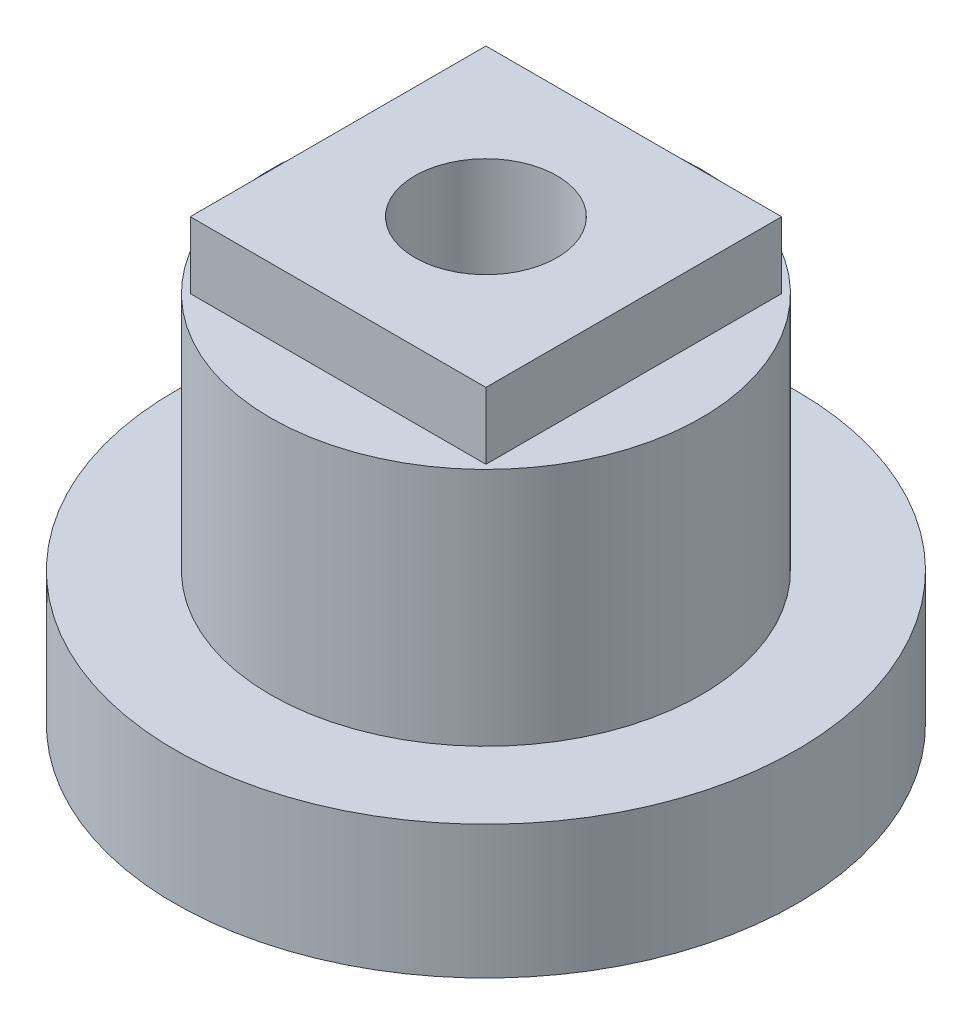
SolidWorks part; units mm, degrees
ref_plane "Alzado" through (0, 0, 0) normal (0, 0, 1) x (1, 0, 0)
ref_plane "Planta" through (0, 0, 0) normal (0, 1, 0) x (1, 0, 0)
ref_plane "Vista lateral" through (0, 0, 0) normal (1, 0, 0) x (0, 0, -1)
sketch "Croquis1" plane through (0, 0, 0) normal (0, 0, 1) x (1, 0, 0)
  line L0 (1.6, 0) -> (7, 0)
  line L1 (7, 0) -> (7, 3)
  line L2 (7, 3) -> (4.85, 3)
  line L3 (4.85, 3) -> (4.85, 8.4)
  line L4 (4.85, 8.4) -> (1.6, 8.4)
  line L6 (0, -1000) -> (0, 49000) construction
  line L7 (1.6, 8.4) -> (1.6, 0)
  line L8 (-1000, 0) -> (49000, 0) construction
  dimension "D1" = 5.4
  dimension "D2" = 14
  dimension "D3" = 9.7
  dimension "D4" = 3
  dimension "D5" = 3.2
revolve "Revolución1" add sketch "Croquis1" angle 360 about L6
sketch "Croquis2" plane through (0, 8.4, 0) normal (0, 1, 0) x (1, 0, 0)
  line L0 (-3.3295, 3.3295) -> (3.3295, 3.3295)
  line L1 (-3.4295, -3.4295) -> (3.4295, -3.4295) construction
  line L2 (-3.4295, -3.4295) -> (-3.4295, 3.4295) construction
  line L3 (-3.4295, 3.4295) -> (3.4295, 3.4295) construction
  line L4 (3.4295, -3.4295) -> (3.4295, 3.4295) construction
  line L5 (-3.4295, -3.4295) -> (3.4295, 3.4295) construction
  line L6 (-3.4295, 3.4295) -> (3.4295, -3.4295) construction
  line L7 (3.3295, -3.3295) -> (3.3295, 3.3295)
  line L8 (-3.3295, -3.3295) -> (3.3295, -3.3295)
  line L9 (-3.3295, -3.3295) -> (-3.3295, 3.3295)
  circle A0 centre (0, 0) radius 1.6 construction
  circle A1 centre (0, 0) radius 1.6
  circle A2 centre (0, 0) radius 4.85 construction
  circle M5 centre (0, 0) radius 1.6
  dimension "D1" = 0.1
extrude "Saliente-Extruir1" add sketch "Croquis2" along normal blind 1.5 contours L1 L4 L3 L2 M5
sketch "Croquis3" plane through (0, 0, 0) normal (0, 1, 0) x (1, 0, 0)
  line L1 (4.65, 0) -> (2.325, 4.027)
  line L2 (2.325, 4.027) -> (-2.325, 4.027)
  line L3 (-2.325, 4.027) -> (-4.65, 0)
  line L4 (-4.65, 0) -> (-2.325, -4.027)
  line L5 (-2.325, -4.027) -> (2.325, -4.027)
  line L6 (2.325, -4.027) -> (4.65, 0)
  circle A0 centre (0, 0) radius 4.027 construction
  dimension "D1" = 9.3
extrude "Cortar-Extruir1" cut sketch "Croquis3" along normal blind 1.5
